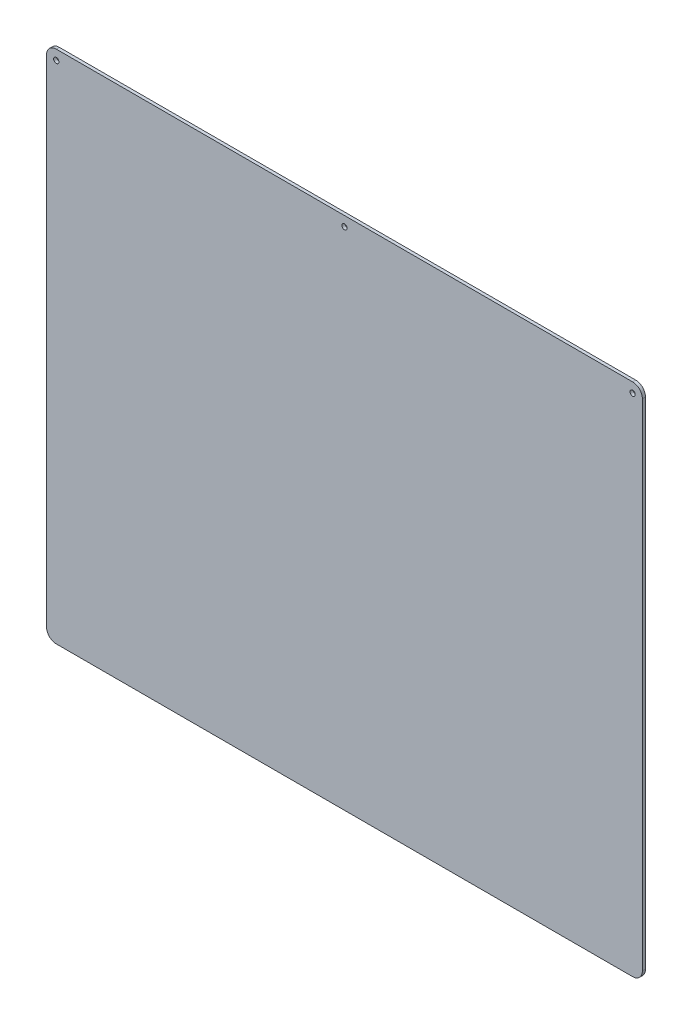
SolidWorks part; units mm, degrees
ref_plane "Front Plane" through (0, 0, 0) normal (0, 0, 1) x (1, 0, 0)
ref_plane "Top Plane" through (0, 0, 0) normal (0, 1, 0) x (1, 0, 0)
ref_plane "Right Plane" through (0, 0, 0) normal (1, 0, 0) x (0, 0, -1)
sketch "Sketch1" plane through (0, 0, 0) normal (0, 0, 1) x (1, 0, 0)
  line L0 (228.102, 462.2676) -> (228.102, -432.1324) construction
  line L1 (-381.498, 137.4676) -> (228.102, 137.4676)
  line L2 (-381.498, 137.4676) -> (-381.498, -389.5084)
  line L3 (-381.498, -389.5084) -> (228.102, -389.5084)
  line L4 (228.102, 137.4676) -> (228.102, -389.5084)
  line L5 (-381.498, -432.1324) -> (-381.498, 462.2676) construction
  dimension "D2" = 526.976
extrude "Boss-Extrude1" add sketch "Sketch1" along normal blind 3.175 contours L1 L4 L3 L2
fillet "Fillet1" radius 10 4 edges at (228.102, -389.5084, 1.5875) (-381.498, -389.5084, 1.5875) (-381.498, 137.4676, 1.5875) (228.102, 137.4676, 1.5875)
sketch "Sketch2" plane through (0, 0, 3.175) normal (0, 0, 1) x (1, 0, 0)
  line L0 (-371.498, 137.4676) -> (218.102, 137.4676) construction
  line L5 (-1247.3405, -361.8084) -> (-1241.3405, -361.8084)
  line L6 (-1249.3405, -363.8084) -> (-1249.3405, -365.2084)
  line L7 (-1247.3405, -367.2084) -> (-1241.3405, -367.2084)
  line L8 (-1239.3405, -363.8084) -> (-1239.3405, -365.2084)
  line L9 (-1249.3405, -361.8084) -> (-1239.3405, -367.2084) construction
  line L10 (-1249.3405, -367.2084) -> (-1239.3405, -361.8084) construction
  line L11 (-651.7405, -367.2084) -> (-657.7405, -367.2084)
  line L12 (-649.7405, -365.2084) -> (-649.7405, -363.8084)
  line L13 (-651.7405, -361.8084) -> (-657.7405, -361.8084)
  line L14 (-659.7405, -365.2084) -> (-659.7405, -363.8084)
  line L15 (-649.7405, -367.2084) -> (-659.7405, -361.8084) construction
  line L16 (-649.7405, -361.8084) -> (-659.7405, -367.2084) construction
  line L17 (-381.498, 127.4676) -> (-381.498, -379.5084) construction
  line L18 (-76.698, 137.4676) -> (-76.698, -389.5084) construction
  line L19 (-371.498, -389.5084) -> (218.102, -389.5084) construction
  line L20 (-371.498, 127.4676) -> (218.102, 127.4676) construction
  circle A0 centre (-654.7405, -364.5084) radius 2.7 construction
  circle A1 centre (-1244.3405, -364.5084) radius 2.7 construction
  circle A2 centre (-654.7405, -364.5084) radius 2.7 construction
  circle A3 centre (-1244.3405, -364.5084) radius 2.7 construction
  arc A4 (-1249.3405, -365.2084) -> (-1247.3405, -367.2084) centre (-1247.3405, -365.2084) ccw
  arc A5 (-1241.3405, -367.2084) -> (-1239.3405, -365.2084) centre (-1241.3405, -365.2084) ccw
  arc A6 (-1241.3405, -361.8084) -> (-1239.3405, -363.8084) centre (-1241.3405, -363.8084) cw
  arc A7 (-1247.3405, -361.8084) -> (-1249.3405, -363.8084) centre (-1247.3405, -363.8084) ccw
  arc A8 (-657.7405, -367.2084) -> (-659.7405, -365.2084) centre (-657.7405, -365.2084) cw
  arc A9 (-651.7405, -367.2084) -> (-649.7405, -365.2084) centre (-651.7405, -365.2084) ccw
  arc A10 (-649.7405, -363.8084) -> (-651.7405, -361.8084) centre (-651.7405, -363.8084) ccw
  arc A11 (-657.7405, -361.8084) -> (-659.7405, -363.8084) centre (-657.7405, -363.8084) ccw
  circle A12 centre (-371.498, 127.4676) radius 2.7
  circle A14 centre (218.102, 127.4676) radius 2.7
  circle A15 centre (-76.698, 127.4676) radius 2.7
  dimension "D2" = 2
  dimension "D4" = 2
  dimension "D5" = 10
  dimension "D6" = 10
  dimension "D7" = 5.4
  dimension "D1" = 10
  dimension "D3" = 10
extrude "Cut-Extrude1" cut sketch "Sketch2" against normal up to surface (3.175 mm away) up to face at (-76.698, -126.0204, 0)
